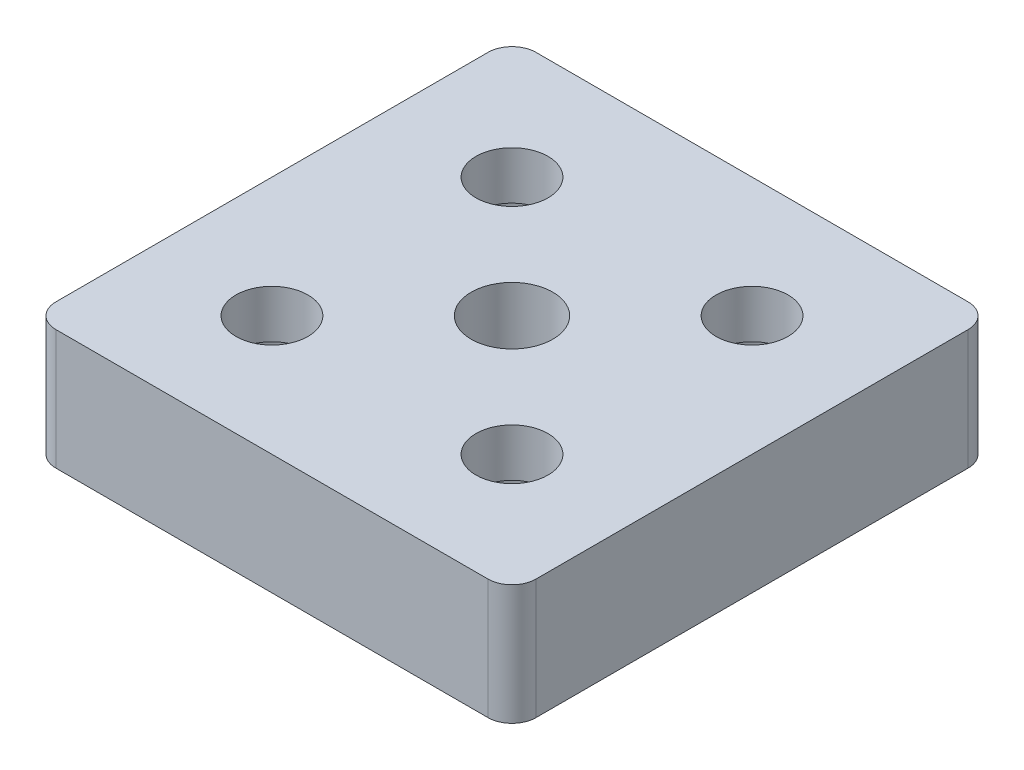
SolidWorks part; units mm, degrees
ref_plane "前视基准面" through (0, 0, 0) normal (0, 0, 1) x (1, 0, 0)
ref_plane "上视基准面" through (0, 0, 0) normal (0, 1, 0) x (1, 0, 0)
ref_plane "右视基准面" through (0, 0, 0) normal (1, 0, 0) x (0, 0, -1)
sketch "草图1" plane through (0, 0, 0) normal (0, 1, 0) x (1, 0, 0)
  line B0 (-18, 0) -> (18, 0)
  line B1 (20, 2) -> (20, 38)
  line B2 (18, 40) -> (-18, 40)
  line B3 (-20, 38) -> (-20, 2)
  arc B4 (18, 0) -> (20, 2) centre (18, 2) ccw
  arc B5 (20, 38) -> (18, 40) centre (18, 38) ccw
  arc B6 (-18, 40) -> (-20, 38) centre (-18, 38) ccw
  arc B7 (-20, 2) -> (-18, 0) centre (-18, 2) ccw
  circle B8 centre (10, 30) radius 3
  circle B9 centre (-10, 30) radius 3
  circle B10 centre (-10, 10) radius 3
  circle B11 centre (10, 10) radius 3
sketch_block_instance "A$C65365DB9-1"
sketch_block "A$C65365DB9"
extrude "凸台-拉伸1" add sketch "草图1" along normal blind 10
sketch "草图3" plane through (0, 0, 0) normal (0, -1, 0) x (1, 0, 0)
  circle A0 centre (-10, -10) radius 5.5
  circle A1 centre (10, -10) radius 5.5
  circle A2 centre (10, -30) radius 5.5
  circle A3 centre (-10, -30) radius 5.5
extrude "切除-拉伸1" cut sketch "草图3" against normal blind 6
sketch "草图4" plane through (0, 10, 0) normal (0, 1, 0) x (1, 0, 0)
  point P0 (0, 20)
hole_wizard "M8 螺纹孔1" positions "3D草图1" profile "草图5" tap size "M8" standard "Iso"
sketch3d "3D草图1"
  point P0 (0, 10, -20)
sketch "草图5" plane through (0, 10, -20) normal (1, 0, 0) x (0, 0, 1)
  line L0 (0, 0) -> (0, 40.7929)
  line L1 (0, 40.7929) -> (3.4, 38.75)
  line L2 (3.4, 38.75) -> (3.4, 0)
  line L5 (3.4, 0) -> (0, 0)
  line L10 (0, 40.7929) -> (-3.4, 38.75) construction
  line L11 (0, -6.35) -> (0, 107.95) construction
  dimension "螺纹孔钻头直径" = 6.8
  dimension "螺纹孔钻头深度" = 38.75
  dimension "导头角度" = 118
cosmetic thread "孔螺蚊线1" parameters "D1"=10, "D2"=8
